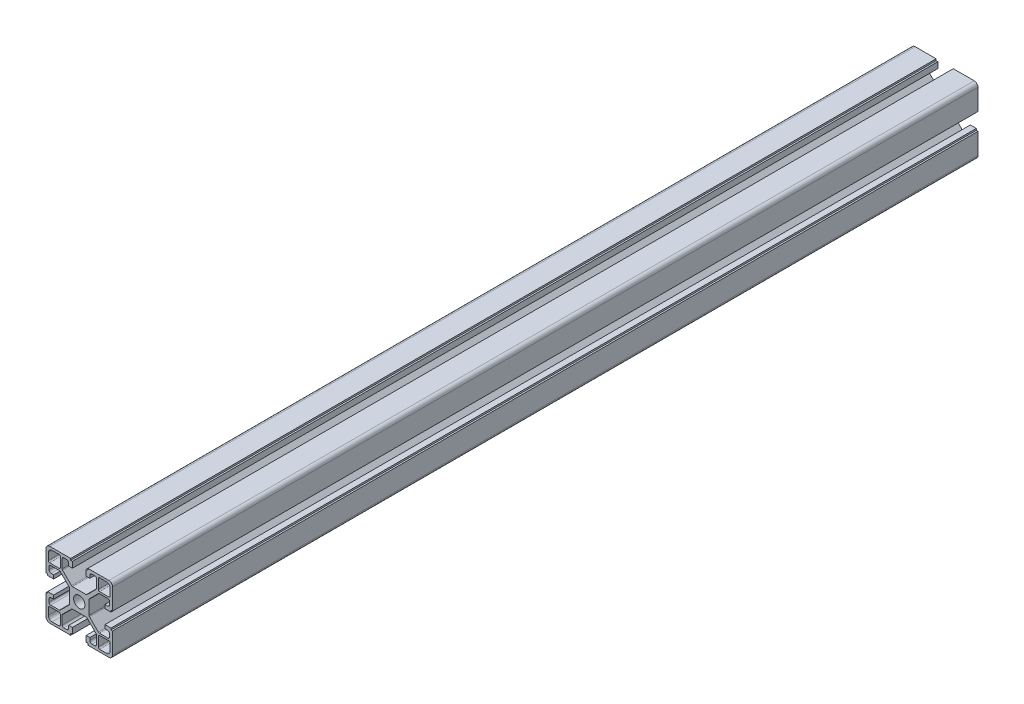
SolidWorks part; units mm, degrees
material "6063-T5"
ref_plane "Front Plane" through (0, 0, 0) normal (0, 0, 1) x (1, 0, 0)
ref_plane "Top Plane" through (0, 0, 0) normal (0, 1, 0) x (1, 0, 0)
ref_plane "Right Plane" through (0, 0, 0) normal (1, 0, 0) x (0, 0, -1)
sketch "Sketch1" plane through (0, 0, 0) normal (0, 0, 1) x (1, 0, 0)
  line L4 (20, 17.75) -> (20, 5.15)
  line L5 (0, -17.7813) -> (0, 18.2) construction
  line L6 (0, 0) -> (38.8613, 0) construction
  line L8 (18.6, 16.35) -> (18.6, 12.2)
  line L10 (11.4, 17.8) -> (11.4, 12.2)
  line L11 (-4.1, 5.85) -> (4.1, 5.85)
  line L14 (5.85, 4.1089) -> (5.85, -4.1089)
  line L17 (12.2, 11.4) -> (17.8, 11.4)
  line L24 (4.15, 19) -> (4.15, 15.4)
  line L25 (4.15, 15.4) -> (6.35, 15.4)
  line L26 (6.35, 15.4) -> (6.35, 16.95)
  line L27 (10.3, 17.2) -> (10.3, 12.0545)
  line L28 (10.0659, 11.489) -> (4.6659, 6.0845)
  line L29 (6.0841, 4.6743) -> (11.4708, 10.0655)
  line L30 (12.0367, 10.3) -> (17.2, 10.3)
  line L31 (18.2, 9.3) -> (18.2, 7.6)
  line L32 (16.95, 6.35) -> (15.4, 6.35)
  line L33 (15.4, 6.35) -> (15.4, 4.15)
  line L34 (15.4, 4.15) -> (19, 4.15)
  line L35 (18.6, 18.6) -> (18.6, -18.6) construction
  line L36 (-18.6, 18.6) -> (18.6, 18.6) construction
  line L37 (-20, 20) -> (20, 20) construction
  line L38 (20, 20) -> (20, -20) construction
  line L40 (7.6, 18.2) -> (9.3, 18.2)
  line L42 (4.15, 19) -> (5.15, 19)
  line L43 (5.15, 19) -> (5.15, 20)
  line L56 (-18.6, 18.6) -> (-18.6, -18.6) construction
  line L57 (-20, 20) -> (-20, -20) construction
  line L60 (5.15, 20) -> (17.75, 20)
  line L91 (-18.6, -18.6) -> (18.6, -18.6) construction
  line L92 (-20, -20) -> (20, -20) construction
  line L93 (12.2, 18.6) -> (16.35, 18.6)
  line L94 (17.9399, 17.9421) -> (20, 20) construction
  line L95 (0, 0) -> (11.4, 11.4094) construction
  line L101 (19, 4.15) -> (19, 5.15)
  line L102 (19, 5.15) -> (20, 5.15)
  line L104 (-5.85, 4.1089) -> (-5.85, -4.1089)
  line L105 (-19, 5.15) -> (-20, 5.15)
  line L106 (-19, 4.15) -> (-19, 5.15)
  line L107 (-12.2, 18.6) -> (-16.35, 18.6)
  line L108 (-5.15, 20) -> (-17.75, 20)
  line L109 (-5.15, 19) -> (-5.15, 20)
  line L110 (-4.15, 19) -> (-5.15, 19)
  line L111 (-7.6, 18.2) -> (-9.3, 18.2)
  line L112 (-15.4, 4.15) -> (-19, 4.15)
  line L113 (-15.4, 6.35) -> (-15.4, 4.15)
  line L114 (-16.95, 6.35) -> (-15.4, 6.35)
  line L115 (-18.2, 9.3) -> (-18.2, 7.6)
  line L116 (-12.0367, 10.3) -> (-17.2, 10.3)
  line L117 (-6.0841, 4.6743) -> (-11.4708, 10.0655)
  line L118 (-10.0659, 11.489) -> (-4.6659, 6.0845)
  line L119 (-10.3, 17.2) -> (-10.3, 12.0545)
  line L120 (-6.35, 15.4) -> (-6.35, 16.95)
  line L121 (-4.15, 15.4) -> (-6.35, 15.4)
  line L122 (-4.15, 19) -> (-4.15, 15.4)
  line L123 (-12.2, 11.4) -> (-17.8, 11.4)
  line L124 (-11.4, 17.8) -> (-11.4, 12.2)
  line L125 (-18.6, 16.35) -> (-18.6, 12.2)
  line L126 (-20, 17.75) -> (-20, 5.15)
  line L127 (-20, -17.75) -> (-20, -5.15)
  line L128 (-18.6, -16.35) -> (-18.6, -12.2)
  line L129 (-11.4, -17.8) -> (-11.4, -12.2)
  line L130 (-12.2, -11.4) -> (-17.8, -11.4)
  line L131 (-4.15, -19) -> (-4.15, -15.4)
  line L132 (-4.15, -15.4) -> (-6.35, -15.4)
  line L133 (-6.35, -15.4) -> (-6.35, -16.95)
  line L134 (-10.3, -17.2) -> (-10.3, -12.0545)
  line L135 (-10.0659, -11.489) -> (-4.6659, -6.0845)
  line L136 (-6.0841, -4.6743) -> (-11.4708, -10.0655)
  line L137 (-12.0367, -10.3) -> (-17.2, -10.3)
  line L138 (-18.2, -9.3) -> (-18.2, -7.6)
  line L139 (-16.95, -6.35) -> (-15.4, -6.35)
  line L140 (-15.4, -6.35) -> (-15.4, -4.15)
  line L141 (-15.4, -4.15) -> (-19, -4.15)
  line L142 (-7.6, -18.2) -> (-9.3, -18.2)
  line L143 (-4.15, -19) -> (-5.15, -19)
  line L144 (-5.15, -19) -> (-5.15, -20)
  line L145 (-5.15, -20) -> (-17.75, -20)
  line L146 (-12.2, -18.6) -> (-16.35, -18.6)
  line L147 (-19, -4.15) -> (-19, -5.15)
  line L148 (-19, -5.15) -> (-20, -5.15)
  line L149 (19, -5.15) -> (20, -5.15)
  line L150 (19, -4.15) -> (19, -5.15)
  line L151 (12.2, -18.6) -> (16.35, -18.6)
  line L152 (5.15, -20) -> (17.75, -20)
  line L153 (5.15, -19) -> (5.15, -20)
  line L154 (4.15, -19) -> (5.15, -19)
  line L155 (7.6, -18.2) -> (9.3, -18.2)
  line L156 (15.4, -4.15) -> (19, -4.15)
  line L157 (15.4, -6.35) -> (15.4, -4.15)
  line L158 (16.95, -6.35) -> (15.4, -6.35)
  line L159 (18.2, -9.3) -> (18.2, -7.6)
  line L160 (12.0367, -10.3) -> (17.2, -10.3)
  line L161 (6.0841, -4.6743) -> (11.4708, -10.0655)
  line L162 (10.0659, -11.489) -> (4.6659, -6.0845)
  line L163 (10.3, -17.2) -> (10.3, -12.0545)
  line L164 (6.35, -15.4) -> (6.35, -16.95)
  line L165 (4.15, -15.4) -> (6.35, -15.4)
  line L166 (4.15, -19) -> (4.15, -15.4)
  line L167 (12.2, -11.4) -> (17.8, -11.4)
  line L168 (-4.1, -5.85) -> (4.1, -5.85)
  line L169 (11.4, -17.8) -> (11.4, -12.2)
  line L170 (18.6, -16.35) -> (18.6, -12.2)
  line L171 (20, -17.75) -> (20, -5.15)
  circle A0 centre (0, 0) radius 3.4
  arc A7 (16.35, 18.6) -> (18.6, 16.35) centre (16.35, 16.35) cw
  arc A8 (20, 17.75) -> (17.75, 20) centre (17.75, 17.75) ccw
  arc A9 (6.35, 16.95) -> (7.6, 18.2) centre (7.6, 16.95) cw
  arc A10 (18.2, 7.6) -> (16.95, 6.35) centre (16.95, 7.6) cw
  arc A11 (17.2, 10.3) -> (18.2, 9.3) centre (17.2, 9.3) cw
  arc A12 (9.3, 18.2) -> (10.3, 17.2) centre (9.3, 17.2) cw
  arc A13 (4.6659, 6.0845) -> (4.1, 5.85) centre (4.1, 6.65) cw
  arc A14 (6.0841, 4.6743) -> (5.85, 4.1089) centre (6.65, 4.1089) ccw
  arc A15 (17.8, 11.4) -> (18.6, 12.2) centre (17.8, 12.2) ccw
  arc A16 (12.2, 18.6) -> (11.4, 17.8) centre (12.2, 17.8) ccw
  arc A17 (11.4, 12.2) -> (12.2, 11.4) centre (12.2, 12.2) ccw
  arc A18 (11.4708, 10.0655) -> (12.0367, 10.3) centre (12.0367, 9.5) cw
  arc A19 (10.3, 12.0545) -> (10.0659, 11.489) centre (9.5, 12.0545) cw
  arc A20 (-10.3, 12.0545) -> (-10.0659, 11.489) centre (-9.5, 12.0545) ccw
  arc A21 (-11.4708, 10.0655) -> (-12.0367, 10.3) centre (-12.0367, 9.5) ccw
  arc A22 (-11.4, 12.2) -> (-12.2, 11.4) centre (-12.2, 12.2) cw
  arc A23 (-12.2, 18.6) -> (-11.4, 17.8) centre (-12.2, 17.8) cw
  arc A24 (-17.8, 11.4) -> (-18.6, 12.2) centre (-17.8, 12.2) cw
  arc A25 (-6.0841, 4.6743) -> (-5.85, 4.1089) centre (-6.65, 4.1089) cw
  arc A26 (-4.6659, 6.0845) -> (-4.1, 5.85) centre (-4.1, 6.65) ccw
  arc A27 (-9.3, 18.2) -> (-10.3, 17.2) centre (-9.3, 17.2) ccw
  arc A28 (-17.2, 10.3) -> (-18.2, 9.3) centre (-17.2, 9.3) ccw
  arc A29 (-18.2, 7.6) -> (-16.95, 6.35) centre (-16.95, 7.6) ccw
  arc A30 (-6.35, 16.95) -> (-7.6, 18.2) centre (-7.6, 16.95) ccw
  arc A31 (-20, 17.75) -> (-17.75, 20) centre (-17.75, 17.75) cw
  arc A32 (-16.35, 18.6) -> (-18.6, 16.35) centre (-16.35, 16.35) ccw
  arc A33 (-16.35, -18.6) -> (-18.6, -16.35) centre (-16.35, -16.35) cw
  arc A34 (-20, -17.75) -> (-17.75, -20) centre (-17.75, -17.75) ccw
  arc A35 (-6.35, -16.95) -> (-7.6, -18.2) centre (-7.6, -16.95) cw
  arc A36 (-18.2, -7.6) -> (-16.95, -6.35) centre (-16.95, -7.6) cw
  arc A37 (-17.2, -10.3) -> (-18.2, -9.3) centre (-17.2, -9.3) cw
  arc A38 (-9.3, -18.2) -> (-10.3, -17.2) centre (-9.3, -17.2) cw
  arc A39 (-4.6659, -6.0845) -> (-4.1, -5.85) centre (-4.1, -6.65) cw
  arc A40 (-6.0841, -4.6743) -> (-5.85, -4.1089) centre (-6.65, -4.1089) ccw
  arc A41 (-17.8, -11.4) -> (-18.6, -12.2) centre (-17.8, -12.2) ccw
  arc A42 (-12.2, -18.6) -> (-11.4, -17.8) centre (-12.2, -17.8) ccw
  arc A43 (-11.4, -12.2) -> (-12.2, -11.4) centre (-12.2, -12.2) ccw
  arc A44 (-11.4708, -10.0655) -> (-12.0367, -10.3) centre (-12.0367, -9.5) cw
  arc A45 (-10.3, -12.0545) -> (-10.0659, -11.489) centre (-9.5, -12.0545) cw
  arc A46 (10.3, -12.0545) -> (10.0659, -11.489) centre (9.5, -12.0545) ccw
  arc A47 (11.4708, -10.0655) -> (12.0367, -10.3) centre (12.0367, -9.5) ccw
  arc A48 (11.4, -12.2) -> (12.2, -11.4) centre (12.2, -12.2) cw
  arc A49 (12.2, -18.6) -> (11.4, -17.8) centre (12.2, -17.8) cw
  arc A50 (17.8, -11.4) -> (18.6, -12.2) centre (17.8, -12.2) cw
  arc A51 (6.0841, -4.6743) -> (5.85, -4.1089) centre (6.65, -4.1089) cw
  arc A52 (4.6659, -6.0845) -> (4.1, -5.85) centre (4.1, -6.65) ccw
  arc A53 (9.3, -18.2) -> (10.3, -17.2) centre (9.3, -17.2) ccw
  arc A54 (17.2, -10.3) -> (18.2, -9.3) centre (17.2, -9.3) ccw
  arc A55 (18.2, -7.6) -> (16.95, -6.35) centre (16.95, -7.6) ccw
  arc A56 (6.35, -16.95) -> (7.6, -18.2) centre (7.6, -16.95) ccw
  arc A57 (20, -17.75) -> (17.75, -20) centre (17.75, -17.75) cw
  arc A58 (16.35, -18.6) -> (18.6, -16.35) centre (16.35, -16.35) ccw
  point P0 (0, 0)
  point P16 (-5.85, 0)
  point P66 (0, 5.85)
  point P120 (5.85, 0)
  point P218 (0, -5.85)
  dimension "D5" = 6.8
  dimension "D6" = 1.4
  dimension "D15" = 5.85
  dimension "D44" = 2.25
  dimension "D25" = 1.25
  dimension "D26" = 1
  dimension "D27" = 0.8
  dimension "D7" = 1.1
  dimension "D8" = 1.1
  dimension "D9" = 1.8
  dimension "D10" = 2.2
  dimension "D11" = 4.6
  dimension "D12" = 1.8
  dimension "D13" = 2.2
  dimension "D14" = 5.85
  dimension "D16" = 1.4
  dimension "D17" = 4.15
  dimension "D18" = 1
  dimension "D19" = 1
  dimension "D20" = 10.3
  dimension "D21" = 4.15
  dimension "D22" = 2
  dimension "D23" = 45.024
  dimension "D24" = 1
  dimension "D41" = 10.3
  dimension "D60" = 14.15
  dimension "D73" = 1
  dimension "D74" = 1
  dimension "D82" = 14.15
  dimension "D3" = 4.6
extrude "Boss-Extrude1" add sketch "Sketch1" along normal blind 713
sketch "Sketch2" plane through (0, 20, 0) normal (0, 1, 0) x (1, 0, 0)
  line L0 (-20, -713) -> (-20, 0) construction
  line L1 (-20, -520) -> (20, -520)
  line L2 (-20, -520) -> (-20, -713)
  line L3 (-20, -713) -> (20, -713)
  line L4 (20, -520) -> (20, -713)
  line L5 (-5.15, 0) -> (-17.75, 0) construction
  dimension "D1" = 520
extrude "Cut-Extrude1" cut sketch "Sketch2" against normal through all
